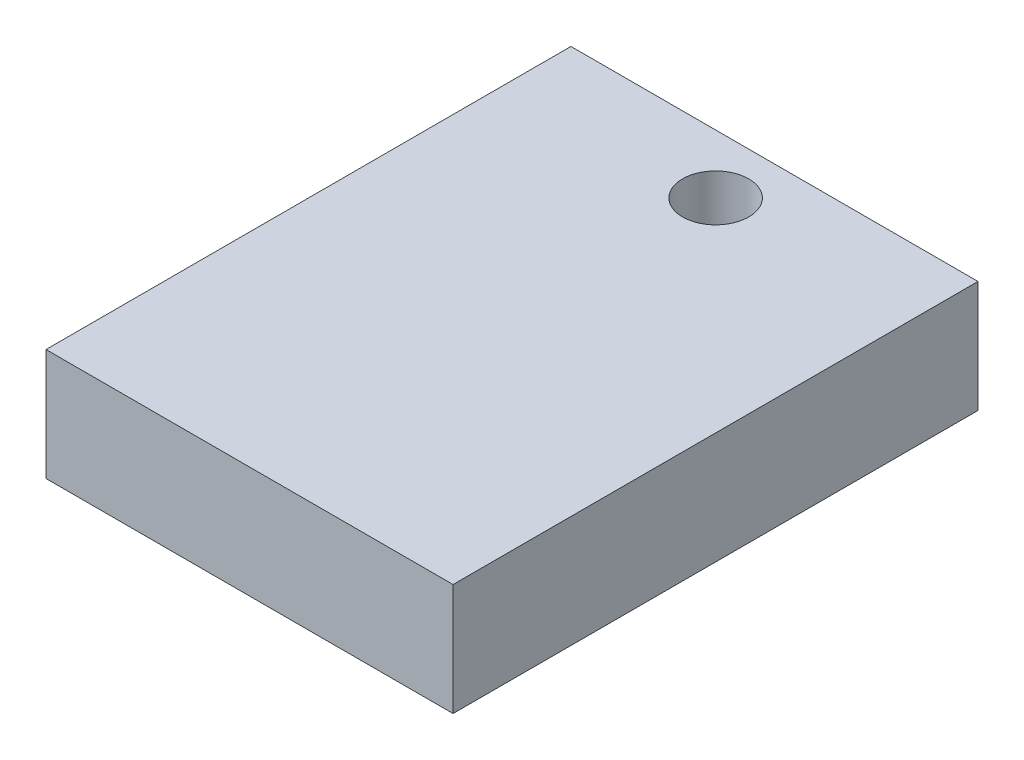
SolidWorks part; units mm, degrees
material "6061 Alloy"
ref_plane "Front Plane" through (0, 0, 0) normal (0, 0, 1) x (1, 0, 0)
ref_plane "Top Plane" through (0, 0, 0) normal (0, 1, 0) x (1, 0, 0)
ref_plane "Right Plane" through (0, 0, 0) normal (1, 0, 0) x (0, 0, -1)
sketch "Sketch1" plane through (0, 0, 0) normal (0, 1, 0) x (1, 0, 0)
  line L1 (0, 0) -> (43.942, 0)
  line L2 (0, 0) -> (0, -56.6674)
  line L3 (0, -56.6674) -> (43.942, -56.6674)
  line L4 (43.942, 0) -> (43.942, -56.6674)
  circle A0 centre (21.971, -6.35) radius 3.57
  point P7 (21.971, 0)
  dimension "D3" = 7.14
  dimension "D1" = 43.942
  dimension "D2" = 56.6674
  dimension "D4" = 6.35
extrude "Boss-Extrude1" add sketch "Sketch1" along normal blind 12.065
